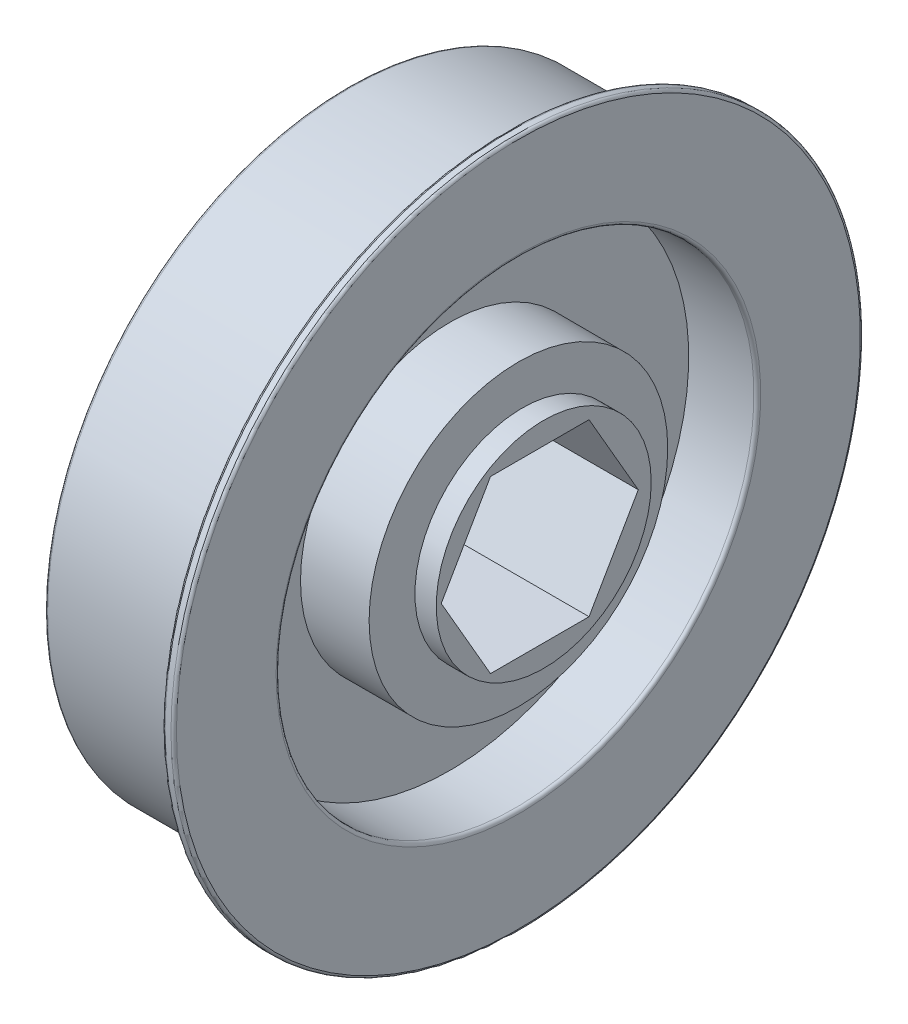
SolidWorks part; units mm, degrees
material "PC High Viscosity"
ref_plane "Front Plane" through (0, 0, 0) normal (0, 0, 1) x (1, 0, 0)
ref_plane "Top Plane" through (0, 0, 0) normal (0, 1, 0) x (1, 0, 0)
ref_plane "Right Plane" through (0, 0, 0) normal (1, 0, 0) x (0, 0, -1)
ref_plane "Plane1" through (0, 0, 0) normal (0, 0, -1) x (-1, 0, 0)
sketch "Sketch1" plane through (0, 0, 0) normal (0, 0, -1) x (-1, 0, 0)
  line L0 (8.4772, 11.1125) -> (3.4226, 11.1125)
  line L1 (3.4226, 11.1125) -> (3.4226, 17.78)
  line L2 (3.4226, 17.78) -> (8.4772, 17.78)
  line L3 (8.7313, 18.034) -> (8.7312, 22.3393)
  line L4 (8.528, 22.5425) -> (-2.2234, 22.5425)
  line L5 (-2.4203, 22.6955) -> (-3.136, 25.501)
  line L6 (-3.3329, 25.654) -> (-3.7655, 25.654)
  line L7 (-3.9687, 25.4508) -> (-3.9687, 18.034)
  line L8 (-3.7147, 17.78) -> (1.1367, 17.78)
  line L9 (1.1367, 17.78) -> (1.1366, 11.1125)
  line L10 (1.1366, 11.1125) -> (-10.1155, 11.1125)
  line L11 (-10.3187, 10.9093) -> (-10.3187, 3.3782)
  line L12 (-10.1155, 3.175) -> (10.1156, 3.175)
  line L13 (10.3188, 3.3782) -> (10.3188, 4.5593)
  line L14 (10.1156, 4.7625) -> (8.7312, 4.7625)
  line L15 (8.7312, 4.7625) -> (8.7312, 10.8585)
  line L16 (-10.3225, 0) -> (10.3225, 0) construction
  arc A0 (8.7312, 10.8585) -> (8.4772, 11.1125) centre (8.4772, 10.8585) ccw
  arc A1 (8.4772, 17.78) -> (8.7313, 18.034) centre (8.4772, 18.034) ccw
  arc A2 (8.7312, 22.3393) -> (8.528, 22.5425) centre (8.528, 22.3393) ccw
  arc A3 (-2.2234, 22.5425) -> (-2.4203, 22.6955) centre (-2.2234, 22.7457) cw
  arc A4 (-3.136, 25.501) -> (-3.3329, 25.654) centre (-3.3329, 25.4508) ccw
  arc A5 (-3.7655, 25.654) -> (-3.9687, 25.4508) centre (-3.7655, 25.4508) ccw
  arc A6 (-3.9687, 18.034) -> (-3.7147, 17.78) centre (-3.7147, 18.034) ccw
  arc A7 (-10.1155, 11.1125) -> (-10.3187, 10.9093) centre (-10.1155, 10.9093) ccw
  arc A8 (-10.3187, 3.3782) -> (-10.1155, 3.175) centre (-10.1155, 3.3782) ccw
  arc A9 (10.1156, 3.175) -> (10.3188, 3.3782) centre (10.1156, 3.3782) ccw
  arc A10 (10.3188, 4.5593) -> (10.1156, 4.7625) centre (10.1156, 4.5593) ccw
revolve "Revolve1" add sketch "Sketch1" angle 360 about L16
sketch "Sketch2" plane through (10.3187, 0, 0) normal (1, 0, 0) x (0, 0, -1)
  circle A0 centre (0, 0) radius 11.1125
  dimension "D1" = 22.225
extrude "Cut-Extrude1" cut sketch "Sketch2" against normal blind 4.7625
sketch "Sketch3" plane through (-10.3188, 0, 0) normal (-1, 0, 0) x (0, 0, 1)
  circle A0 centre (0, 0) radius 11.1125
  dimension "D1" = 22.225
extrude "Cut-Extrude2" cut sketch "Sketch3" against normal blind 3.175
sketch "Sketch4" plane through (-7.1438, 0, 0) normal (-1, 0, 0) x (0, 0, 1)
  line L1 (3.6662, 6.35) -> (-3.6662, 6.35)
  line L2 (-3.6662, 6.35) -> (-7.3323, 0)
  line L3 (-7.3323, 0) -> (-3.6662, -6.35)
  line L4 (-3.6662, -6.35) -> (3.6662, -6.35)
  line L5 (3.6662, -6.35) -> (7.3323, 0)
  line L6 (7.3323, 0) -> (3.6662, 6.35)
  circle A0 centre (0, 0) radius 6.35 construction
  dimension "D1" = 12.7
extrude "Cut-Extrude3" cut sketch "Sketch4" against normal through all
sketch "Sketch5" plane through (5.5562, 0, 0) normal (1, 0, 0) x (0, 0, -1)
  circle A0 centre (0.2963, 0) radius 8
  circle A2 centre (0, 0) radius 11.1125
  circle A3 centre (0, 0) radius 11.1125
  dimension "D1" = 16
  dimension "D2" = 0
extrude "Cut-Extrude4" cut sketch "Sketch5" against normal blind 1.5875
